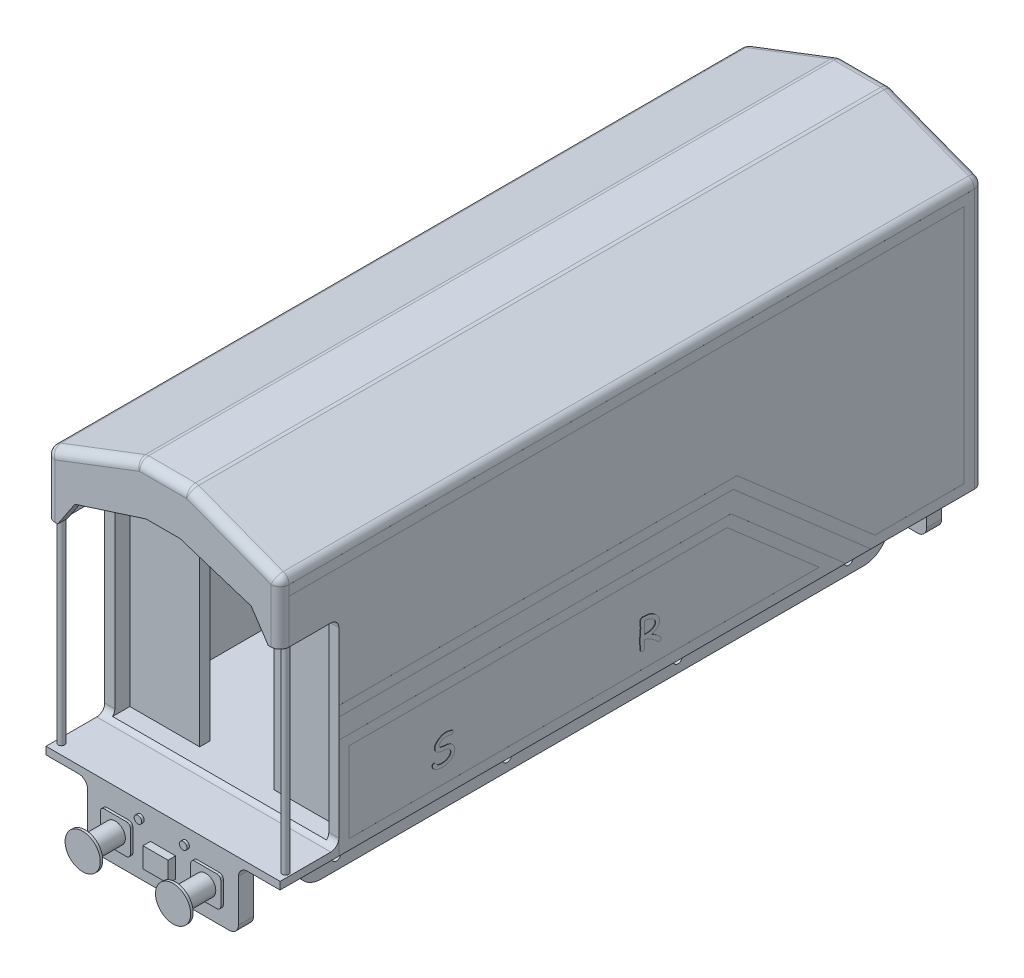
SolidWorks part; units mm, degrees
ref_plane "Front Plane" through (0, 0, 0) normal (0, 0, 1) x (1, 0, 0)
ref_plane "Top Plane" through (0, 0, 0) normal (0, 1, 0) x (1, 0, 0)
ref_plane "Right Plane" through (0, 0, 0) normal (1, 0, 0) x (0, 0, -1)
sketch "Sketch1" plane through (0, 0, 0) normal (0, 0, 1) x (1, 0, 0)
  line L0 (-2330, 0) -> (2330, 0)
  line L1 (2330, 0) -> (2330, 5300)
  line L2 (-500, 6000) -> (500, 6000)
  line L3 (-2330, 5300) -> (-2330, 0)
  line L4 (-2330, 5300) -> (-500, 6000)
  line L5 (500, 6000) -> (2330, 5300)
  dimension "D1" = 4660
  dimension "D2" = 5300
  dimension "D3" = 500
  dimension "D4" = 6000
extrude "Boss-Extrude1" add sketch "Sketch1" along normal blind 14000
shell "Shell1" thickness 200
sketch "Sketch4" plane through (0, 0, 0) normal (1, 0, 0) x (0, 0, -1)
  line L0 (-14000, 0) -> (0, 0) construction
  line L1 (-14390.4253, 4100) -> (-12990.4253, 4100)
  line L2 (-14390.4253, 4100) -> (-14390.4253, 150)
  line L3 (-14390.4253, 150) -> (-12990.4253, 150)
  line L4 (-12830.4253, 3940) -> (-12830.4253, 310)
  line L5 (-14000, 5300) -> (0, 5300) construction
  arc A0 (-12990.4253, 150) -> (-12830.4253, 310) centre (-12990.4253, 310) ccw
  arc A1 (-12990.4253, 4100) -> (-12830.4253, 3940) centre (-12990.4253, 3940) cw
  dimension "D3" = 160
  dimension "D1" = 150
  dimension "D2" = 1200
  dimension "D4" = 1400
extrude "Cut-Extrude1" cut sketch "Sketch4" against normal mid plane 6000
sketch "Sketch5" plane through (0, 0, 14000) normal (0, 0, 1) x (1, 0, 0)
  line L0 (-1380, 5173.2527) -> (1380, 5173.2527) construction
  line L1 (-2130, 4046.4179) -> (-1380, 5173.2527) construction
  line L2 (2130, 200) -> (2130, 5162.3704) construction
  line L4 (2130, 4046.4179) -> (1380, 5173.2527) construction
  line L5 (-1755, 4609.8353) -> (-337.1945, 5065.0013)
  line L6 (337.1945, 5065.0013) -> (1755, 4609.8353)
  line L7 (-1755, 4609.8353) -> (-2130, 4046.4179)
  line L8 (1755, 4609.8353) -> (2130, 4046.4179)
  line L9 (2130, 5173.2527) -> (32.9113, 6105.9395) construction
  line L10 (32.9113, 6105.9395) -> (-2130, 5173.2527) construction
  line L11 (-337.1945, 5065.0013) -> (337.1945, 5065.0013)
  line L12 (-2130, 4046.4179) -> (2130, 4046.4179)
  dimension "D1" = 750
  dimension "D2" = 750
extrude "Cut-Extrude2" cut sketch "Sketch5" against normal up to next
sketch "Sketch6" plane through (0, 4100, 0) normal (0, -1, 0) x (1, 0, 0)
  circle A0 centre (-2230, 13792.3751) radius 65
  circle A1 centre (2230, 13792.3751) radius 65
  dimension "D1" = 130
extrude "Boss-Extrude3" add sketch "Sketch6" along normal up to next
sketch "Sketch8" plane through (0, 0, 0) normal (0, -1, 0) x (-1, 0, 0)
  line L1 (1500, -14000) -> (-1500, -14000)
  line L2 (1500, -14000) -> (1500, -13700)
  line L3 (1500, -13700) -> (-1500, -13700)
  line L4 (-1500, -14000) -> (-1500, -13700)
  line L8 (2330, -14000) -> (-2330, -14000) construction
  dimension "D1" = 3000
  dimension "D2" = 300
extrude "Boss-Extrude4" add sketch "Sketch8" along normal blind 1200
sketch "Sketch9" plane through (0, 0, 14000) normal (0, 0, 1) x (1, 0, 0)
  line L0 (1500, -1200) -> (1500, 0) construction
  line L1 (1120, -300) -> (680, -300)
  line L2 (1200, -380) -> (1200, -820)
  line L3 (1120, -900) -> (680, -900)
  line L4 (600, -380) -> (600, -820)
  line L5 (1500, 0) -> (2330, 0) construction
  arc A0 (600, -820) -> (680, -900) centre (680, -820) ccw
  arc A1 (1120, -900) -> (1200, -820) centre (1120, -820) ccw
  arc A2 (1200, -380) -> (1120, -300) centre (1120, -380) ccw
  arc A3 (680, -300) -> (600, -380) centre (680, -380) ccw
  point P10 (600, -900)
  point P15 (1200, -300)
  point P18 (600, -300)
  dimension "D5" = 80
  dimension "D1" = 600
  dimension "D2" = 600
  dimension "D3" = 300
  dimension "D4" = 300
extrude "Boss-Extrude5" add sketch "Sketch9" along normal blind 50
sketch "Sketch10" plane through (0, 0, 14050) normal (0, 0, 1) x (1, 0, 0)
  circle A0 centre (900, -600) radius 200
  dimension "D1" = 400
extrude "Boss-Extrude6" add sketch "Sketch10" along normal blind 500
sketch "Sketch11" plane through (0, 0, 14550) normal (0, 0, 1) x (1, 0, 0)
  circle A0 centre (900, -600) radius 125
  dimension "D1" = 250
extrude "Boss-Extrude7" add sketch "Sketch11" along normal blind 100
sketch "Sketch12" plane through (0, 0, 14650) normal (0, 0, 1) x (1, 0, 0)
  circle A0 centre (900, -600) radius 350
  dimension "D1" = 700
extrude "Boss-Extrude8" add sketch "Sketch12" along normal blind 50
mirror "Mirror2" about plane through (0, 0, 0) normal (1, 0, 0) of "Boss-Extrude8", "Boss-Extrude7", "Boss-Extrude6", "Boss-Extrude5"
sketch "Sketch13" plane through (0, 0, 14000) normal (0, 0, 1) x (1, 0, 0)
  line L0 (-2330, 150) -> (2330, 150) construction
  line L1 (0, 0) -> (0, -321.9349) construction
  line L2 (-450, -150) -> (0, -150) construction
  circle A0 centre (-450, -150) radius 75
  dimension "D1" = 150
  dimension "D2" = 300
  dimension "D3" = 450
extrude "Boss-Extrude9" add sketch "Sketch13" along normal blind 50 contours A0
mirror "Mirror3" about plane through (0, 0, 0) normal (1, 0, 0) of "Boss-Extrude9"
sketch "Sketch14" plane through (0, 0, 14000) normal (0, 0, 1) x (1, 0, 0)
  line L0 (-2330, 150) -> (2330, 150) construction
  line L1 (-250, -450) -> (250, -450)
  line L2 (-250, -450) -> (-250, -850)
  line L3 (-250, -850) -> (250, -850)
  line L4 (250, -450) -> (250, -850)
  line L5 (-250, -450) -> (250, -850) construction
  line L6 (-250, -850) -> (250, -450) construction
  point P0 (0, -650)
  dimension "D1" = 500
  dimension "D2" = 400
  dimension "D3" = 600
extrude "Boss-Extrude10" add sketch "Sketch14" along normal blind 150
ref_plane "Plane1" through (0, 0, 7000) normal (0, 0, -1) x (-1, 0, 0)
mirror "Mirror4" about plane through (0, 0, 7000) normal (0, 0, -1) of "Boss-Extrude4", "Boss-Extrude8", "Boss-Extrude6", "Boss-Extrude7", "Boss-Extrude5", "Boss-Extrude10", "Mirror3", "Boss-Extrude9", "Mirror2"
sketch "Sketch15" plane through (0, 0, 0) normal (0, 0, -1) x (-1, 0, 0)
  line L1 (-900, 200) -> (900, 200)
  line L2 (-900, 200) -> (-900, 4200)
  line L3 (-900, 4200) -> (900, 4200)
  line L4 (900, 200) -> (900, 4200)
  dimension "D1" = 200
  dimension "D2" = 1800
  dimension "D3" = 4000
  dimension "D4" = 900
extrude "Cut-Extrude3" [suppressed] cut sketch "Sketch15" against normal up to next
sketch "Sketch17" plane through (0, 0, 0) normal (0, -1, 0) x (1, 0, 0)
  line L0 (-2330, 14000) -> (-2330, 0) construction
  line L1 (-1550, 12900) -> (-1400, 12900)
  line L2 (-1550, 12900) -> (-1550, 1100)
  line L3 (-1550, 1100) -> (-1400, 1100)
  line L4 (-1400, 12900) -> (-1400, 1100)
  line L5 (-1500, 13700) -> (1500, 13700) construction
  line L6 (-1500, 300) -> (1500, 300) construction
  dimension "D1" = 780
  dimension "D2" = 150
  dimension "D3" = 800
  dimension "D4" = 800
extrude "Boss-Extrude11" add sketch "Sketch17" along normal blind 1000
fillet "Fillet1" radius 500 2 edges at (-1475, -1000, 12900) (-1475, -1000, 1100)
sketch "Sketch19" plane through (-1550, 0, 0) normal (-1, 0, 0) x (0, 0, 1)
  line L0 (1100, -500) -> (1100, 0) construction
  line L1 (12400, -1000) -> (1600, -1000) construction
  line L2 (1900, -750) -> (5300, -750) construction
  circle A0 centre (1900, -750) radius 90
  circle A1 centre (5300, -750) radius 90
  circle A2 centre (8700, -750) radius 90
  circle A3 centre (12100, -750) radius 90
  dimension "D1" = 180
  dimension "D2" = 800
  dimension "D3" = 250
  dimension "D5" = 3400
  dimension "D4" = 4
extrude "Cut-Extrude5" cut sketch "Sketch19" against normal up to next
mirror "Mirror5" about plane through (0, 0, 0) normal (1, 0, 0) of "Fillet1", "Boss-Extrude11", "Cut-Extrude5"
sketch "Sketch20" plane through (2130, 0, 0) normal (-1, 0, 0) x (0, 0, 1)
  line L0 (14000, 5300) -> (0, 5300) construction
  line L1 (12530.4253, 5300) -> (12330.4253, 5300)
  line L2 (12530.4253, 5300) -> (12530.4253, 0)
  line L3 (12530.4253, 0) -> (12330.4253, 0)
  line L4 (12330.4253, 5300) -> (12330.4253, 0)
  line L5 (14000, 0) -> (0, 0) construction
  line L6 (12830.4253, 310) -> (12830.4253, 3940) construction
  dimension "D1" = 300
  dimension "D2" = 200
extrude "Boss-Extrude12" add sketch "Sketch20" along normal blind 1391
mirror "Mirror7" about plane through (0, 0, 0) normal (1, 0, 0) of "Boss-Extrude12"
sketch "Sketch21" plane through (-2330, 0, 0) normal (-1, 0, 0) x (0, 0, 1)
  line L0 (12830.4253, 310) -> (12830.4253, 3940) construction
  line L1 (12830.4253, 2397.3023) -> (4977.7427, 2397.3023)
  line L2 (12830.4253, 2397.3023) -> (12830.4253, 2000)
  line L3 (12830.4253, 2000) -> (5024.1199, 2000)
  line L5 (4977.7427, 2397.3023) -> (2237.0132, 0)
  line L6 (14000, 0) -> (0, 0) construction
  line L7 (5024.1199, 2000) -> (2737.6085, 0)
  line L8 (12900, 0) -> (1100, 0) construction
  line L9 (2737.6085, 0) -> (2237.0132, 0)
  dimension "D1" = 400
  dimension "D2" = 2000
split line "Split Line1"
fillet "Fillet2" radius 180 8 edges at (-1500, 0, 150) (1500, 0, 150) (-1500, -1200, 13850) (1500, -1200, 13850) (1500, -1200, 150) (-1500, -1200, 150)
fillet "Fillet3" radius 180 14 edges at (2330, 5300, 7000) (1415, 5650, 14000) (1415, 5650, 0) (500, 6000, 7000) (0, 6000, 14000) (0, 6000, 0) (-500, 6000, 7000) (-1415, 5650, 14000) (-2330, 5300, 7000) (-1415, 5650, 0) (2330, 4700, 14000) (-2330, 4700, 14000) (2330, 2650, 0) (-2330, 2650, 0)
sketch "Sketch22" plane through (0, 0, 0) normal (0, 0, -1) x (-1, 0, 0)
  line L0 (2150, 150) -> (-2150, 150)
  line L1 (2150, 0) -> (2150, 5176.1333) construction
  line L2 (-2150, 5176.1333) -> (-2150, 0) construction
  line L3 (2150, 0) -> (1680, 0) construction
  dimension "D1" = 150
extrude "Extrude-Thin1" add sketch "Sketch22" along normal blind 0.1 thin
sketch "Sketch23" plane through (2330, 0, 0) normal (1, 0, 0) x (0, 0, -1)
  line L0 (-380, 4976.1333) -> (-13620, 4976.1333)
  line L1 (-12830.4253, 2397.3023) -> (-12830.4253, 2597.3023)
  line L2 (-12830.4253, 3940) -> (-12830.4253, 2397.3023) construction
  line L3 (-12830.4253, 2597.3023) -> (-12630.4253, 2597.3023)
  line L4 (-12630.4253, 2597.3023) -> (-4902.6154, 2597.3023)
  line L5 (-4902.6154, 2597.3023) -> (-2161.8859, 200)
  line L6 (-2161.8859, 200) -> (-380, 200)
  line L7 (-380, 200) -> (-380, 4976.1333)
  line L8 (-180, 5176.1333) -> (-13820, 5176.1333)
  line L9 (-13820, 5176.1333) -> (-13820, 4100)
  line L10 (-13820, 4100) -> (-12990.4253, 4100)
  line L11 (-12830.4253, 3940) -> (-12830.4253, 2397.3023)
  line L12 (-12830.4253, 2397.3023) -> (-4977.7427, 2397.3023)
  line L13 (-4977.7427, 2397.3023) -> (-2237.0132, 0)
  line L14 (-2237.0132, 0) -> (-180, 0)
  line L15 (-180, 0) -> (-180, 5176.1333)
  line L16 (-180, 5176.1333) -> (-13820, 5176.1333)
  line L17 (-13820, 5176.1333) -> (-13820, 4976.1333)
  line L18 (-13820, 5176.1333) -> (-13820, 4100) construction
  line L19 (-13820, 4976.1333) -> (-13620, 4976.1333)
  line L20 (-12830.4253, 2397.3023) -> (-4977.7427, 2397.3023)
  line L21 (-4977.7427, 2397.3023) -> (-2237.0132, 0)
  line L22 (-2237.0132, 0) -> (-180, 0)
  line L23 (-180, 0) -> (-180, 5176.1333)
  line L32 (-12830.4253, 3940) -> (-12830.4253, 2397.3023) construction
  line L33 (-12630.4253, 3940) -> (-12630.4253, 2597.3023) construction
  line L34 (-13820, 4100) -> (-12990.4253, 4100) construction
  line L35 (-13820, 5176.1333) -> (-13820, 4100) construction
  line L36 (-13620, 4976.1333) -> (-13620, 4300) construction
  line L37 (-13620, 4300) -> (-12990.4253, 4300) construction
  arc A1 (-12830.4253, 3940) -> (-12990.4253, 4100) centre (-12990.4253, 3940) ccw
  arc A4 (-12630.4253, 3940) -> (-12990.4253, 4300) centre (-12990.4253, 3940) ccw construction
  arc A5 (-12830.4253, 3940) -> (-12990.4253, 4100) centre (-12990.4253, 3940) ccw construction
  dimension "D1" = 0
  dimension "D2" = 200
extrude "Boss-Extrude13" add sketch "Sketch23" along normal blind 0.1
sketch "Sketch25" plane through (2330, 0, 0) normal (1, 0, 0) x (0, 0, -1)
  line L0 (-12830.4253, 310) -> (-12830.4253, 0)
  line L1 (-12630.4253, 310) -> (-12630.4253, 200)
  line L2 (-12630.4253, 200) -> (-3270.0381, 200)
  line L3 (-3270.0381, 200) -> (-5099.2472, 1800)
  line L4 (-5099.2472, 1800) -> (-12630.4253, 1800)
  line L5 (-12630.4253, 1800) -> (-12630.4253, 310)
  line L6 (-2737.6085, 0) -> (-5024.1199, 2000)
  line L7 (-5024.1199, 2000) -> (-12830.4253, 2000)
  line L8 (-12830.4253, 2000) -> (-12830.4253, 310)
  line L9 (-12990.4253, 150) -> (-14000, 150)
  line L10 (-14000, 150) -> (-14000, 0)
  line L11 (-14000, 0) -> (-2737.6085, 0)
  line L12 (-2737.6085, 0) -> (-5024.1199, 2000)
  line L13 (-5024.1199, 2000) -> (-12830.4253, 2000)
  line L14 (-12830.4253, 2000) -> (-12830.4253, 310)
  line L17 (-12830.4253, 0) -> (-2737.6085, 0)
  arc A1 (-12990.4253, 150) -> (-12830.4253, 310) centre (-12990.4253, 310) ccw
  dimension "D1" = 0
  dimension "D2" = 200
extrude "Boss-Extrude14" add sketch "Sketch25" along normal blind 0.1
mirror "Mirror8" about plane through (0, 0, 0) normal (1, 0, 0) of "Boss-Extrude13", "Boss-Extrude14"
sketch "Sketch26" plane through (2330, 0, 0) normal (1, 0, 0) x (0, 0, -1)
  line L0 (-11575.73, 531.5769) -> (-5856.0675, 531.5769) construction
  text T0 "S                R" font "Comic Sans MS" height in points 2000
extrude "Boss-Extrude15" add sketch "Sketch26" along normal blind 10
sketch "Sketch27" plane through (-2330, 0, 0) normal (-1, 0, 0) x (0, 0, 1)
  line L0 (5017.1836, 506.1562) -> (12109.5652, 506.1562) construction
  text T0 "S                 R" font "Century Gothic" height in points 2000
extrude "Boss-Extrude16" add sketch "Sketch27" along normal blind 10
